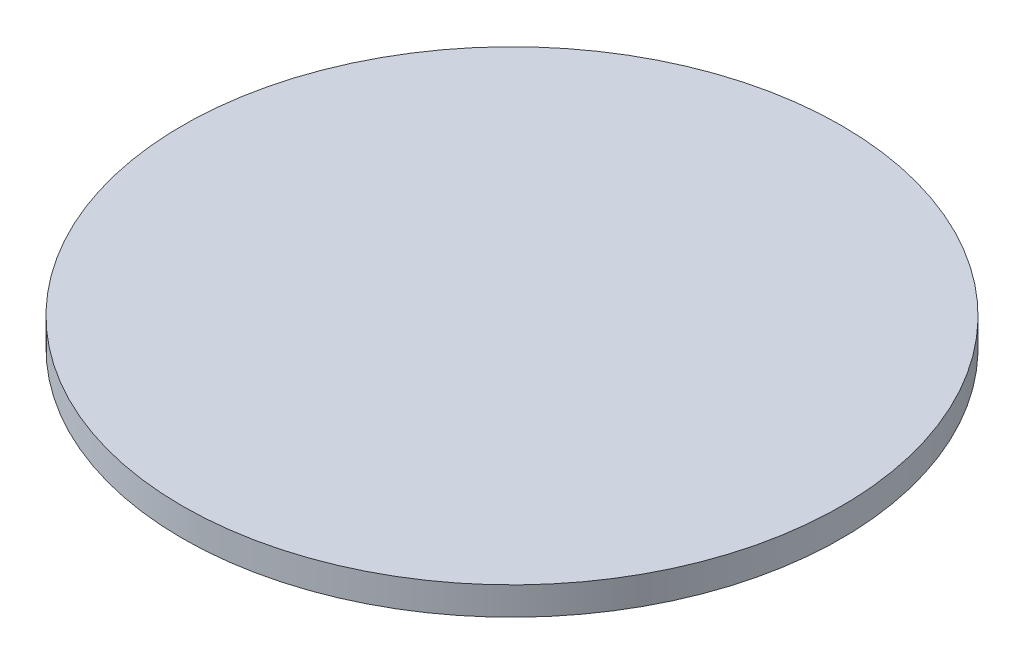
SolidWorks part; units mm, degrees
ref_plane "Front Plane" through (0, 0, 0) normal (0, 0, 1) x (1, 0, 0)
ref_plane "Top Plane" through (0, 0, 0) normal (0, 1, 0) x (1, 0, 0)
ref_plane "Right Plane" through (0, 0, 0) normal (1, 0, 0) x (0, 0, -1)
sketch "Sketch1" plane through (0, 0, 0) normal (0, 1, 0) x (1, 0, 0)
  circle A0 centre (0, 0) radius 149.225
  dimension "D1" = 298.45
extrude "Boss-Extrude1" add sketch "Sketch1" along normal blind 12.7
sketch "Sketch3" plane through (0, 12.7, 0) normal (0, 1, 0) x (1, 0, 0)
  line L0 (0, 105) -> (0, -105) construction
  line L1 (-105, -105) -> (105, -105)
  line L2 (-105, -105) -> (-105, 105)
  line L3 (-105, 105) -> (105, 105)
  line L4 (105, -105) -> (105, 105)
  line L5 (-105, -105) -> (105, 105) construction
  line L6 (-105, 105) -> (105, -105) construction
  line L7 (-105, 0) -> (105, 0) construction
  point P0 (0, 0)
  dimension "D1" = 210
